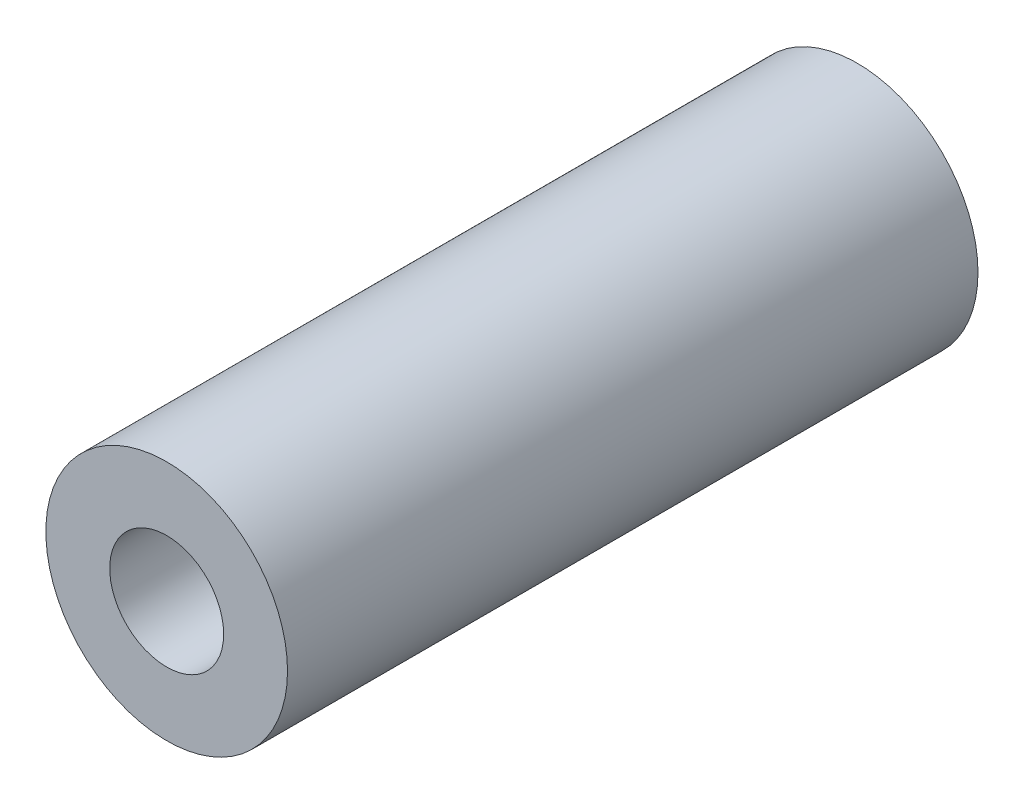
SolidWorks part; units mm, degrees
material "6061 合金"
ref_plane "前视基准面" through (0, 0, 0) normal (0, 0, 1) x (1, 0, 0)
ref_plane "上视基准面" through (0, 0, 0) normal (0, 1, 0) x (1, 0, 0)
ref_plane "右视基准面" through (0, 0, 0) normal (1, 0, 0) x (0, 0, -1)
sketch "草图1" plane through (0, 0, 0) normal (0, 0, 1) x (1, 0, 0)
  circle A1 centre (0, 0) radius 3.5
  dimension "D1" = 7
extrude "凸台-拉伸1" add sketch "草图1" along normal blind 20
hole_wizard "M4 螺纹孔1" positions "草图2" profile "草图3" tap size "M4" standard "GB" end condition through all
sketch "草图2" plane through (0, 0, 20) normal (0, 0, 1) x (1, 0, 0)
  point P0 (0, 0)
sketch "草图3" plane through (0, 0, 20) normal (1, 0, 0) x (0, -1, 0)
  line L0 (0, 0) -> (0, 20)
  line L1 (0, 20) -> (1.65, 20)
  line L2 (1.65, 20) -> (1.65, 0)
  line L5 (1.65, 0) -> (0, 0)
  line L11 (0, -6.35) -> (0, 107.95) construction
  dimension "通孔螺纹孔钻头直径" = 3.3
  dimension "通孔螺纹孔钻头深度" = 20
cosmetic thread "孔螺蚊线1" parameters "D2"=4
